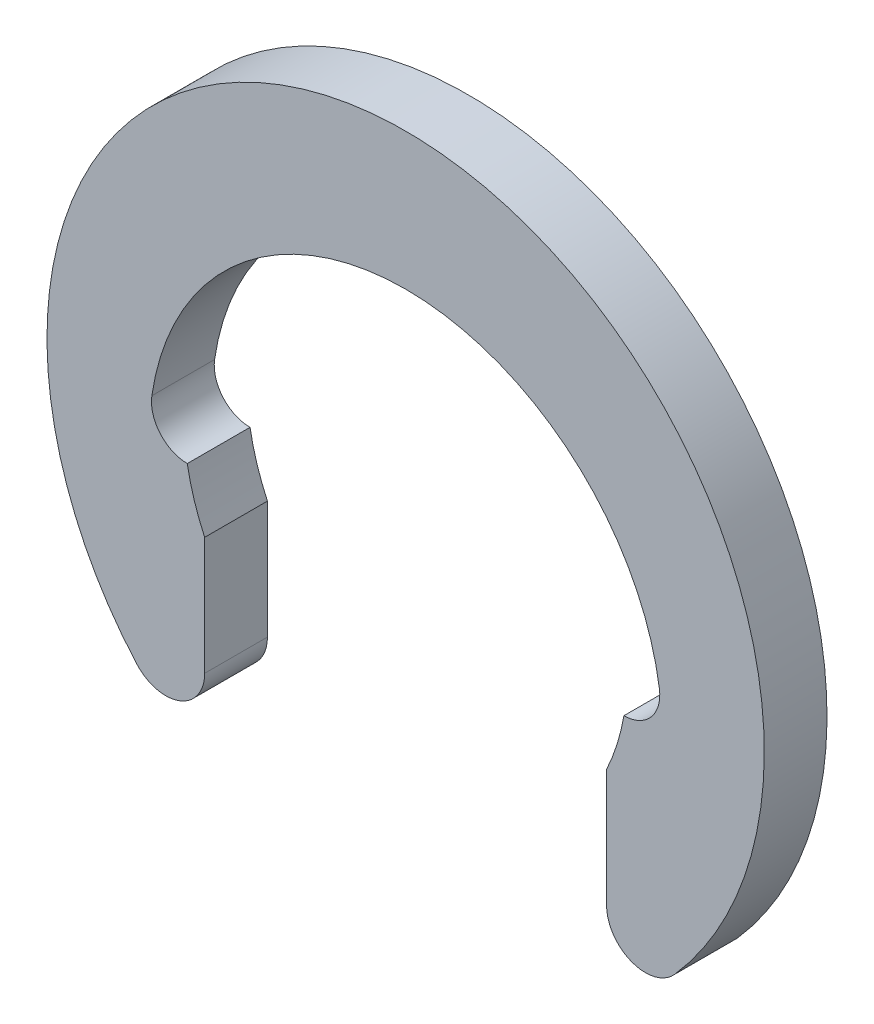
SolidWorks part; units mm, degrees
ref_plane "Plane1" through (0, 0, 0) normal (0, 0, 1) x (1, 0, 0)
ref_plane "Plane2" through (0, 0, 0) normal (0, 1, 0) x (1, 0, 0)
ref_plane "Plane3" through (0, 0, 0) normal (1, 0, 0) x (0, 0, -1)
sketch "Clipboard" plane through (0, 0, 0) normal (0, 0, 1) x (1, 0, 0)
  line L0 (0, 0) -> (0.7874, 0)
  circle A0 centre (0, 0) radius 1.2954
  circle A1 centre (0, 0) radius 2.0955
  dimension "FreeID" = 2.5908
  dimension "FreeOD" = 4.191
  dimension "LargeSection" = 0.7874
sketch "BodySke" plane through (0, 0, 0) normal (0, 0, 1) x (1, 0, 0)
  line L0 (-1.5431, 0) -> (1.5431, 0) construction
  line L1 (0, 0) -> (0, 1.3462) construction
  line L2 (0, 0) -> (1.3257, -0.2338) construction
  line L3 (0, 0) -> (1.2201, -0.5689) construction
  line L4 (0, 0) -> (-1.3257, -0.2338) construction
  line L5 (0, 0) -> (-1.2201, -0.5689) construction
  line L6 (1.2201, -0.5689) -> (1.2201, -1.2839)
  line L7 (-1.2201, -0.5689) -> (-1.2201, -1.2839)
  circle A0 centre (0, 0) radius 1.3462 construction
  arc A1 (1.5431, 0) -> (-1.5431, 0) centre (0, -0.2112) ccw construction
  arc A2 (1.6335, -1.4401) -> (-1.6335, -1.4401) centre (0, 0) ccw
  arc A3 (1.2201, -0.5689) -> (1.3257, -0.2338) centre (0, 0) ccw
  arc A4 (1.5409, 0.0153) -> (-1.5409, 0.0153) centre (0, -0.2112) ccw
  arc A5 (-1.3257, -0.2338) -> (-1.2201, -0.5689) centre (0, 0) ccw
  arc A6 (1.3257, -0.2338) -> (1.5409, 0.0153) centre (1.3257, -0.0163) ccw
  arc A7 (-1.5409, 0.0153) -> (-1.3257, -0.2338) centre (-1.3257, -0.0163) ccw
  arc A8 (1.2201, -1.2839) -> (1.6335, -1.4401) centre (1.4563, -1.2839) ccw
  arc A9 (-1.6335, -1.4401) -> (-1.2201, -1.2839) centre (-1.4563, -1.2839) ccw
  dimension "GrooveDia" = 2.6924
  dimension "OutsideDia" = 4.3554
  dimension "TipRad" = 0.2362
  dimension "CavityWidth" = 3.0861
  dimension "D1" = 10
  dimension "D2" = 15
extrude "Body" add sketch "BodySke" against normal blind 0.381
equation "' \"FreeID@Clipboard\" = 0.102"
equation "' \"Thickness@Body\" = 0.015"
equation "' \"GrooveDia@BodySke\" = 0.106"
equation "' \"FreeOD@Clipboard\" = 0.165"
equation "' \"LargeSection@Clipboard\" = 0.031"
equation "\"OutsideDia@BodySke\" = ( \"GrooveDia@BodySke\"  /  \"FreeID@Clipboard\" )  * \"FreeOD@Clipboard\""
equation "\"CavityWidth@BodySke\" = \"GrooveDia@BodySke\" + 0.25 * 2 * \"LargeSection@Clipboard\""
equation "\"TipRad@BodySke\" = 0.3 * \"LargeSection@Clipboard\""
